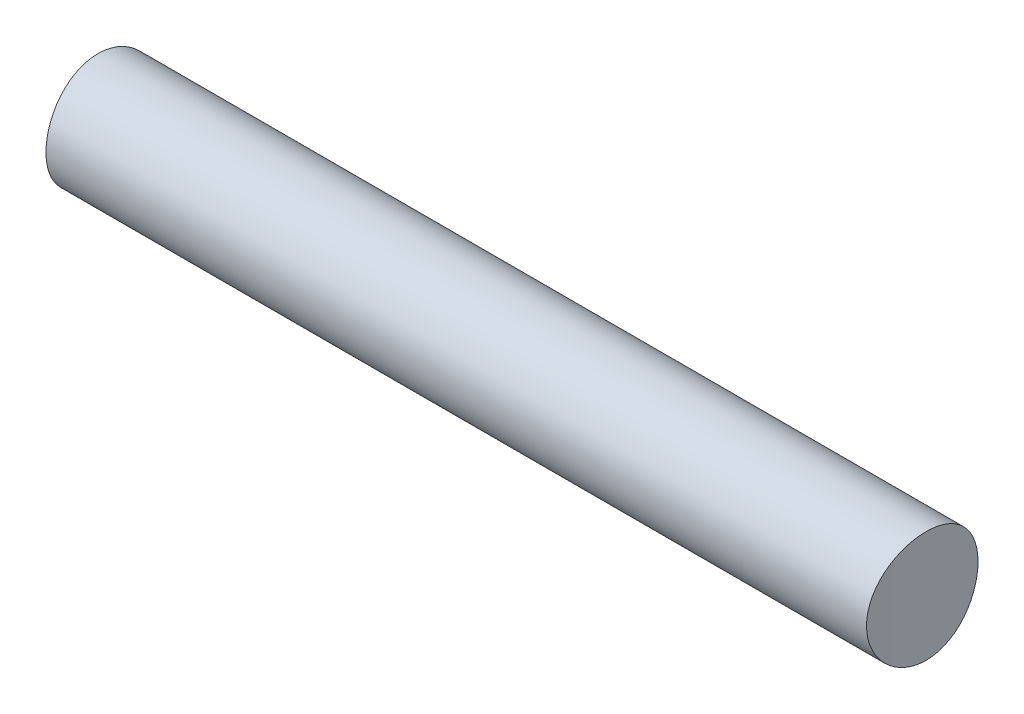
SolidWorks part; units mm, degrees
ref_plane "Front Plane" through (0, 0, 0) normal (0, 0, 1) x (1, 0, 0)
ref_plane "Top Plane" through (0, 0, 0) normal (0, 1, 0) x (1, 0, 0)
ref_plane "Right Plane" through (0, 0, 0) normal (1, 0, 0) x (0, 0, -1)
sketch "Sketch1" plane through (0, 0, 0) normal (1, 0, 0) x (0, 0, -1)
  circle A0 centre (0, 0) radius 50.8
  dimension "D1" = 101.6
extrude "Boss-Extrude1" add sketch "Sketch1" along normal mid plane 754.38
sketch "Sketch2" plane through (0, 0, 0) normal (0, 1, 0) x (1, 0, 0)
  line L0 (-377.19, 50.8) -> (414.1548, 50.8)
  line L1 (414.1548, 50.8) -> (414.1548, -50.8)
  line L2 (414.1548, -50.8) -> (377.19, -50.8)
  line L3 (377.19, -50.8) -> (-403.1266, -50.8)
  line L4 (-377.19, -50.8) -> (377.19, -50.8) construction
  line L5 (-377.19, 50.8) -> (-403.1266, 50.8)
  line L6 (-403.1266, 50.8) -> (-403.1266, -50.8)
  circle A0 centre (0, 0) radius 377.19
  dimension "D1" = 754.38
extrude "Cut-Extrude1" cut sketch "Sketch2" against normal through all both and the other way through all contours A0 L0 L5 L6 L3 | A0 L3 L2 L1 L0
